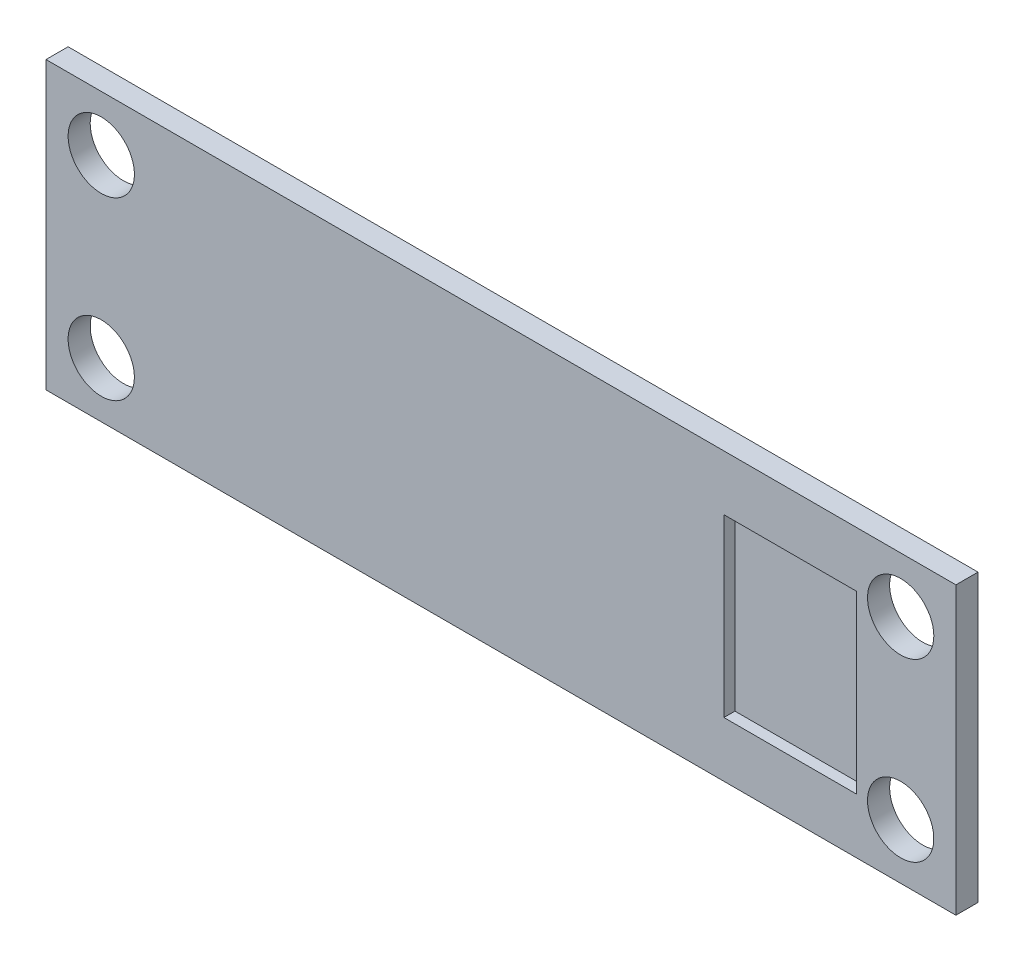
SolidWorks part; units mm, degrees
ref_plane "Alzado" through (0, 0, 0) normal (0, 0, 1) x (1, 0, 0)
ref_plane "Planta" through (0, 0, 0) normal (0, 1, 0) x (1, 0, 0)
ref_plane "Vista lateral" through (0, 0, 0) normal (1, 0, 0) x (0, 0, -1)
sketch "Croquis1" plane through (0, 0, 0) normal (0, 0, 1) x (1, 0, 0)
  line L0 (-20.59, 12.95) -> (-20.59, 0) construction
  line L1 (0, 0) -> (-41.18, 0)
  line L2 (0, 0) -> (0, 12.95)
  line L3 (0, 12.95) -> (-41.18, 12.95)
  line L4 (-41.18, 0) -> (-41.18, 12.95)
  line L5 (-41.18, 6.475) -> (0, 6.475) construction
  circle A0 centre (-38.68, 2.5) radius 1.5
  circle A1 centre (-38.68, 10.45) radius 1.5
  circle A2 centre (-2.5, 2.5) radius 1.5
  circle A3 centre (-2.5, 10.45) radius 1.5
  dimension "D3" = 3
  dimension "D4" = 2.5
  dimension "D5" = 2.5
  dimension "D1" = 41.18
  dimension "D2" = 12.95
extrude "Saliente-Extruir1" add sketch "Croquis1" along normal blind 1
sketch "Croquis2" plane through (0, 0, 1) normal (0, 0, 1) x (1, 0, 0)
  line L0 (-4, 10.45) -> (-4.5, 10.45) construction
  line L2 (-4.5, 10.45) -> (-4.5, 2.5)
  line L3 (-4.5, 2.5) -> (-10.5, 2.5)
  line L4 (-10.5, 2.5) -> (-10.5, 10.45)
  line L5 (-10.5, 10.45) -> (-4.5, 10.45)
  circle A0 centre (-2.5, 10.45) radius 1.5 construction
  circle A2 centre (-2.5, 2.5) radius 1.5 construction
  dimension "D1" = 6
  dimension "D2" = 0
  dimension "D3" = 0.5
extrude "Cortar-Extruir1" cut sketch "Croquis2" against normal blind 0.5
